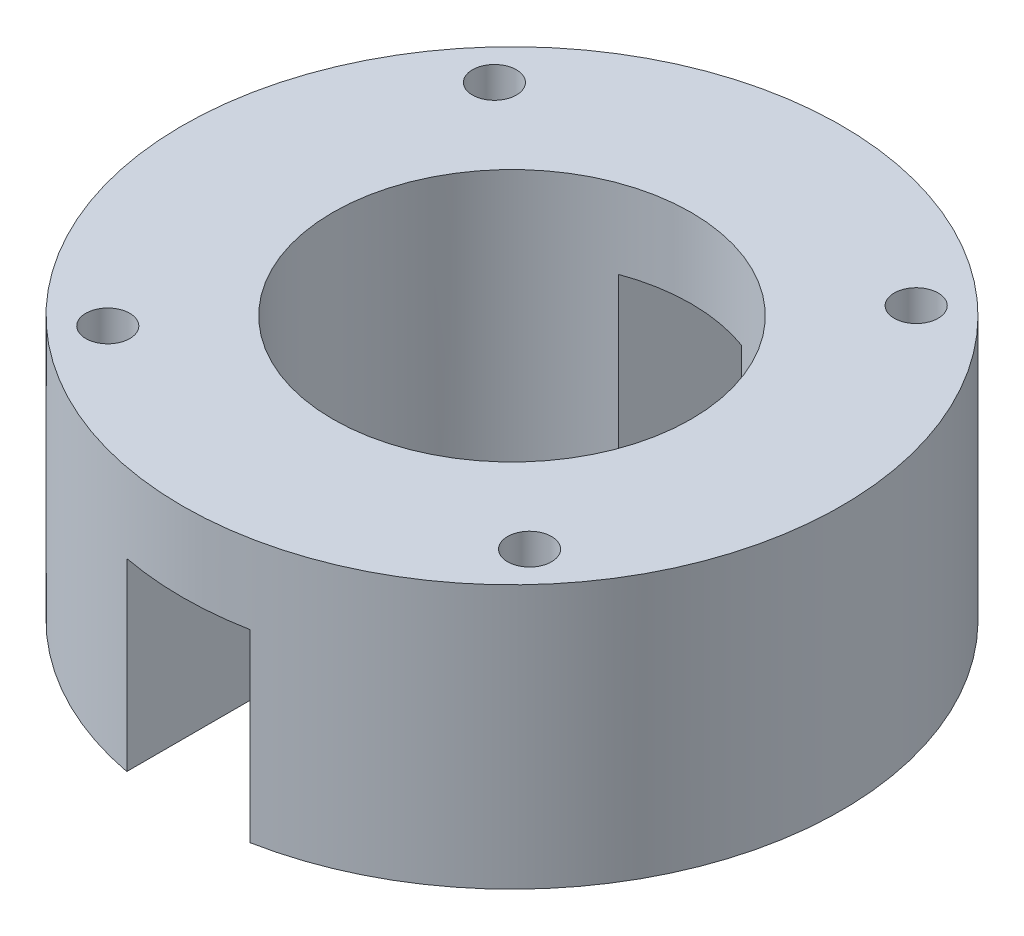
SolidWorks part; units mm, degrees
ref_plane "Front Plane" through (0, 0, 0) normal (0, 0, 1) x (1, 0, 0)
ref_plane "Top Plane" through (0, 0, 0) normal (0, 1, 0) x (1, 0, 0)
ref_plane "Right Plane" through (0, 0, 0) normal (1, 0, 0) x (0, 0, -1)
sketch "Sketch2" plane through (0, 0, 0) normal (0, 1, 0) x (1, 0, 0)
  circle A0 centre (0, 0) radius 37.5
  dimension "D1" = 75
extrude "Boss-Extrude1" add sketch "Sketch2" along normal blind 30
sketch "Sketch3" plane through (0, 30, 0) normal (0, 1, 0) x (1, 0, 0)
  point P14 (0, 0)
sketch "Sketch4" plane through (0, 30, 0) normal (0, 1, 0) x (1, 0, 0)
  circle A0 centre (22, 24) radius 2.5
  circle A1 centre (24, -22) radius 2.5
  circle A2 centre (-22, -24) radius 2.5
  circle A3 centre (-24, 22) radius 2.5
  point P12 (0, 0)
  dimension "D1" = 24
  dimension "5" = 5
  dimension "D2" = 22
  dimension "D3" = 4
extrude "Cut-Extrude2" cut sketch "Sketch4" against normal blind 25
sketch "Sketch5" plane through (0, 0, 0) normal (0, 0, 1) x (1, 0, 0)
  line L1 (7, -21) -> (-7, -21)
  line L2 (7, -21) -> (7, 21)
  line L3 (7, 21) -> (-7, 21)
  line L4 (-7, -21) -> (-7, 21)
  line L5 (7, -21) -> (-7, 21) construction
  line L6 (7, 21) -> (-7, -21) construction
  point P0 (0, 0)
  dimension "D1" = 14
  dimension "D2" = 42
extrude "Cut-Extrude3" cut sketch "Sketch5" against normal mid plane 115
sketch "Sketch6" plane through (0, 30, 0) normal (0, 1, 0) x (1, 0, 0)
  circle A0 centre (0, 0) radius 20.3855
extrude "Cut-Extrude4" cut sketch "Sketch6" against normal mid plane 115
sketch "Sketch7" plane through (0, 0, 0) normal (1, 0, 0) x (0, 0, -1)
  circle A0 centre (0, 25) radius 2.5
  dimension "D1" = 5
  dimension "D2" = 25
sketch "Sketch8" plane through (0, 0, 0) normal (0, 0, 1) x (1, 0, 0)
  circle A0 centre (0, 25) radius 2.5
  dimension "D1" = 5
  dimension "D2" = 25
